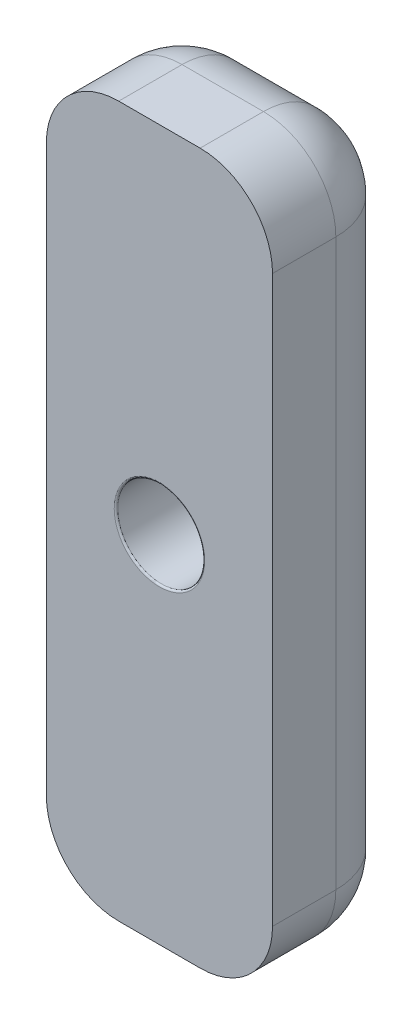
SolidWorks part; units mm, degrees
ref_plane "Front Plane" through (0, 0, 0) normal (1, 0, 0) x (0, 1, 0)
ref_plane "Top Plane" through (0, 0, 0) normal (0, 0, 1) x (0, 1, 0)
ref_plane "Right Plane" through (0, 0, 0) normal (0, 1, 0) x (-1, 0, 0)
sketch "Sketch1" plane through (0, 0, 0) normal (0, 0, 1) x (0, 1, 0)
  line L1 (-39.25, -12.5) -> (39.25, -12.5)
  line L2 (-39.25, -12.5) -> (-39.25, 12.5)
  line L3 (-39.25, 12.5) -> (39.25, 12.5)
  line L4 (39.25, -12.5) -> (39.25, 12.5)
  line L5 (-39.25, -12.5) -> (39.25, 12.5) construction
  line L6 (-39.25, 12.5) -> (39.25, -12.5) construction
  circle A0 centre (0, 0) radius 4.8 construction
  dimension "D1" = 9.6
  dimension "D2" = 25
  dimension "D3" = 78.5
extrude "Boss-Extrude1" add sketch "Sketch1" along normal blind 15
sketch "Sketch2" plane through (0, 0, 15) normal (0, 0, 1) x (1, 0, 0)
  circle A0 centre (0, 0) radius 4.8
extrude "Cut-Extrude1" cut sketch "Sketch2" against normal blind 13
fillet "Fillet1" radius 0.2 1 edges at (4.8, 0, 15)
fillet "Fillet2" radius 8 4 edges at (-12.5, -39.25, 7.5) (12.5, -39.25, 7.5) (12.5, 39.25, 7.5) (-12.5, 39.25, 7.5)
fillet "Fillet3" radius 8 8 edges at (10.1569, -36.9069, 0) (12.5, 0, 0) (10.1569, 36.9069, 0) (0, 39.25, 0) (-10.1569, 36.9069, 0) (-12.5, 0, 0) (-10.1569, -36.9069, 0) (0, -39.25, 0)
